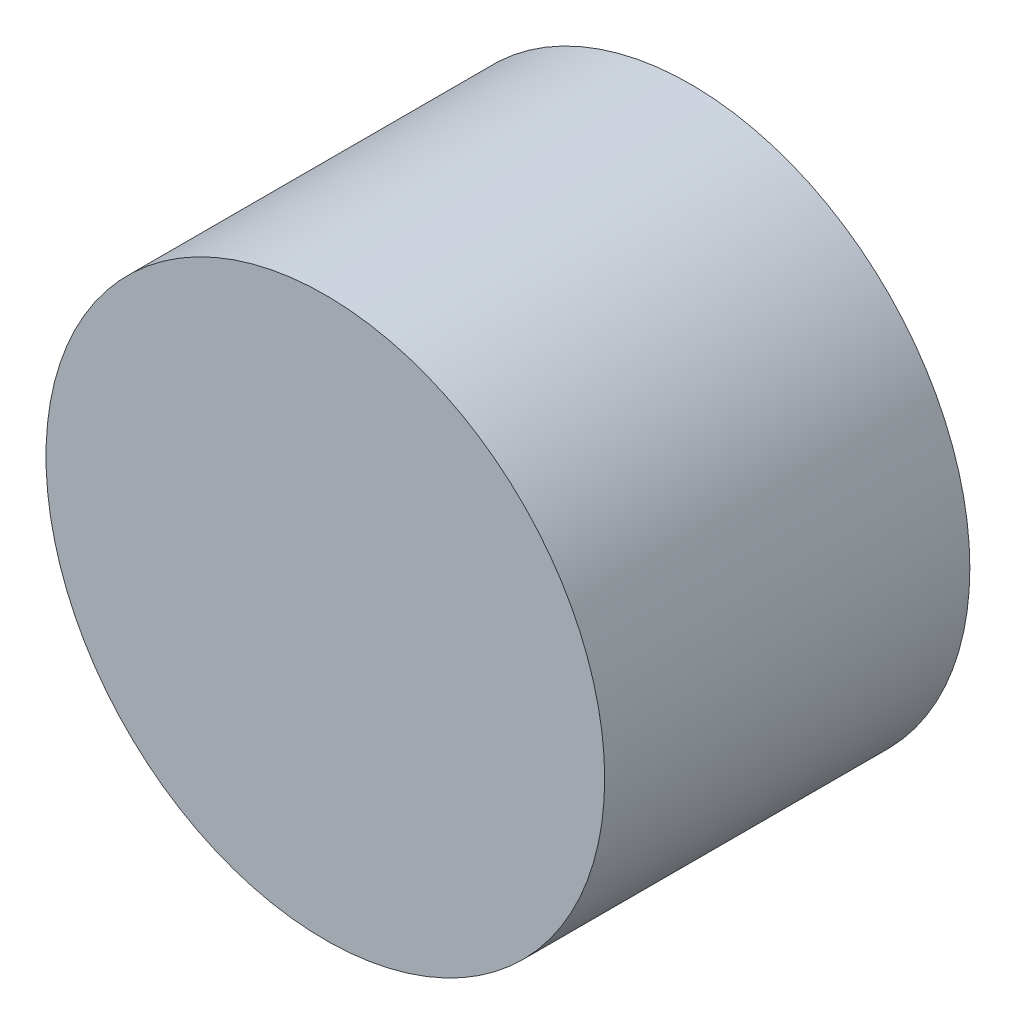
SolidWorks part; units mm, degrees
ref_plane "前视基准面" through (0, 0, 0) normal (0, 0, 1) x (1, 0, 0)
ref_plane "上视基准面" through (0, 0, 0) normal (0, 1, 0) x (1, 0, 0)
ref_plane "右视基准面" through (0, 0, 0) normal (1, 0, 0) x (0, 0, -1)
other "Configuration Table"
sketch "草图1" plane through (0, 0, 0) normal (0, 0, 1) x (1, 0, 0)
  circle A0 centre (0, 0) radius 35
extrude "外形" add sketch "草图1" along normal blind 45.75 from offset 0
